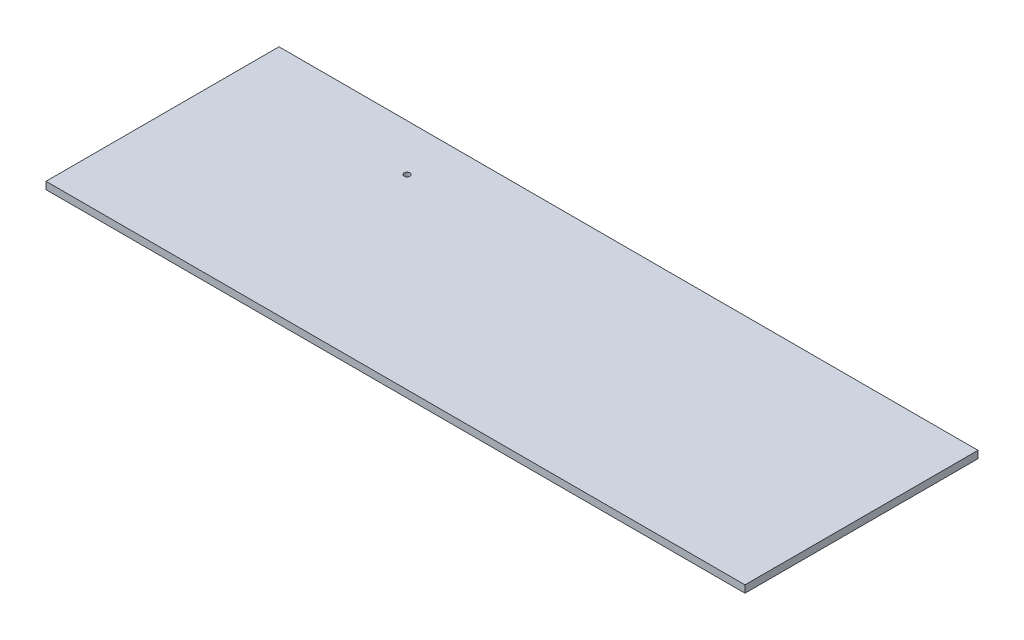
SolidWorks part; units mm, degrees
ref_plane "Front Plane" through (0, 0, 0) normal (0, 0, 1) x (1, 0, 0)
ref_plane "Top Plane" through (0, 0, 0) normal (0, 1, 0) x (1, 0, 0)
ref_plane "Right Plane" through (0, 0, 0) normal (1, 0, 0) x (0, 0, -1)
sketch "Sketch1" plane through (0, 0, 0) normal (0, 1, 0) x (1, 0, 0)
  line L1 (0, 0) -> (304.8, 0)
  line L2 (0, 0) -> (0, -101.6)
  line L3 (0, -101.6) -> (304.8, -101.6)
  line L4 (304.8, 0) -> (304.8, -101.6)
  dimension "D1" = 304.8
  dimension "D2" = 101.6
extrude "Boss-Extrude1" add sketch "Sketch1" along normal blind 3.175
sketch "Sketch3" plane through (0, 3.175, 0) normal (0, 1, 0) x (1, 0, 0)
  line L0 (0, 0) -> (0, -101.6) construction
  line L1 (304.8, 0) -> (0, 0) construction
  circle A0 centre (76.2, -20.32) radius 1.27
  dimension "D1" = 2.54
  dimension "D2" = 76.2
  dimension "D3" = 20.32
extrude "Cut-Extrude1" cut sketch "Sketch3" against normal blind 2.54
sketch "Sketch4" plane through (0, 0.635, 0) normal (0, 1, 0) x (1, 0, 0)
  circle A0 centre (76.2, -20.32) radius 1.3029
extrude "Cut-Extrude2" cut sketch "Sketch4" against normal blind 12.7
